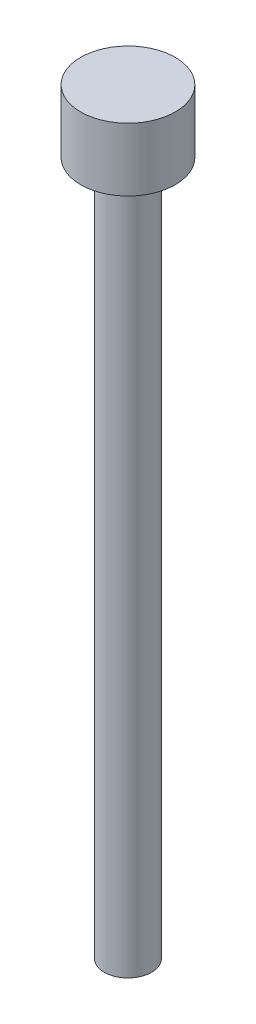
SolidWorks part; units mm, degrees
ref_plane "Front Plane" through (0, 0, 0) normal (0, 0, 1) x (1, 0, 0)
ref_plane "Top Plane" through (0, 0, 0) normal (0, 1, 0) x (1, 0, 0)
ref_plane "Right Plane" through (0, 0, 0) normal (1, 0, 0) x (0, 0, -1)
sketch "Sketch1" plane through (0, 0, 0) normal (0, 1, 0) x (1, 0, 0)
  circle A0 centre (0, 0) radius 4.7625
extrude "Boss-Extrude1" add sketch "Sketch1" along normal blind 6.35 contours A0
sketch "Sketch2" plane through (0, 0, 0) normal (0, -1, 0) x (-1, 0, 0)
  circle A0 centre (0, 0) radius 2.3813
extrude "Boss-Extrude2" add sketch "Sketch2" along normal blind 69.85
